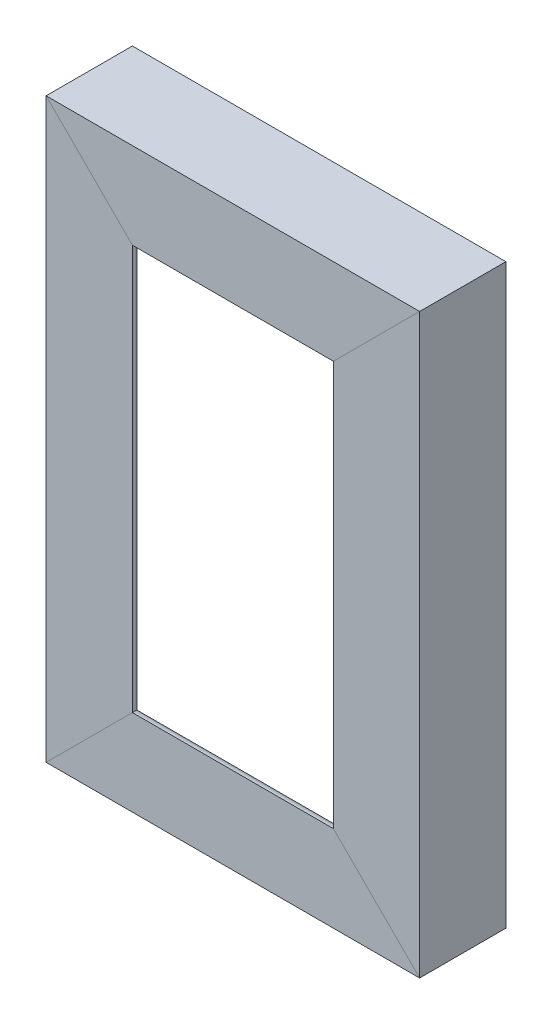
SolidWorks part; units mm, degrees
ref_plane "Alzado" through (0, 0, 0) normal (0, 0, 1) x (1, 0, 0)
ref_plane "Planta" through (0, 0, 0) normal (0, 1, 0) x (1, 0, 0)
ref_plane "Vista lateral" through (0, 0, 0) normal (1, 0, 0) x (0, 0, -1)
sketch "Croquis1" plane through (0, 0, 0) normal (0, 0, 1) x (1, 0, 0)
  line L1 (55, -85) -> (-55, -85)
  line L2 (55, -85) -> (55, 85)
  line L3 (55, 85) -> (-55, 85)
  line L4 (-55, -85) -> (-55, 85)
  line L5 (55, -85) -> (-55, 85) construction
  line L6 (55, 85) -> (-55, -85) construction
  point P0 (0, 0)
  dimension "D1" = 170
  dimension "D2" = 110
other "Hierro angular 1 X 1 X 0.125(1)"
ref_plane "Plano1" through (-55, -85, 0) normal (0, 1, 0) x (1, 0, 0)
sketch "Sketch1" plane through (-55, -85, 0) normal (0, 1, 0) x (1, 0, 0)
  line L0 (0, 0) -> (0, 25.4)
  line L1 (0, 25.4) -> (0.0051, 25.4)
  line L2 (3.175, 22.2301) -> (3.175, 7.9375)
  line L3 (7.9375, 3.175) -> (22.2301, 3.175)
  line L4 (25.4, 0.0051) -> (25.4, 0)
  line L5 (25.4, 0) -> (0, 0)
  arc A0 (25.4, 0.0051) -> (22.2301, 3.175) centre (22.2301, 0.0051) ccw
  arc A1 (0.0051, 25.4) -> (3.175, 22.2301) centre (0.0051, 22.2301) cw
  arc A2 (7.9375, 3.175) -> (3.175, 7.9375) centre (7.9375, 7.9375) cw
  point P10 (12.7, 0)
  point P14 (0, 12.7)
  point P15 (3.175, 12.7)
  point P16 (12.7, 3.175)
  point P17 (3.175, 25.4)
  point P18 (25.4, 3.175)
  point P19 (0, 0)
  dimension "D2" = 0.0051
  dimension "Radius_1" = 4.7625
  dimension "D1" = 3.175
  dimension "H_leg" = 25.4
